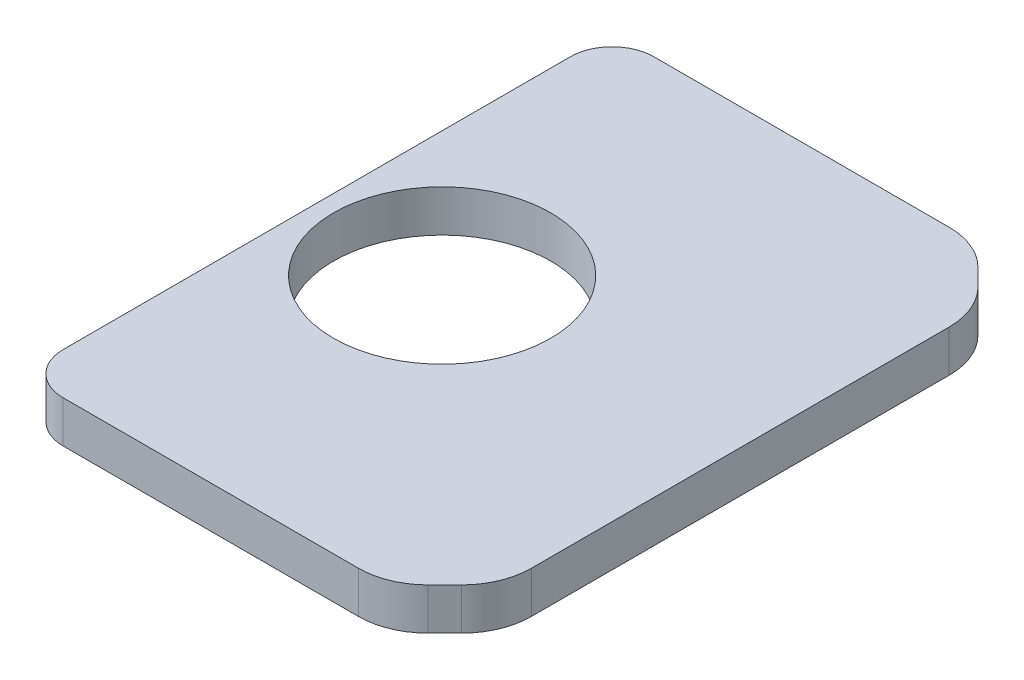
SolidWorks part; units mm, degrees
material "ABS"
ref_plane "Płaszczyzna przednia" through (0, 0, 0) normal (0, 0, 1) x (1, 0, 0)
ref_plane "Płaszczyzna górna" through (0, 0, 0) normal (0, 1, 0) x (1, 0, 0)
ref_plane "Płaszczyzna prawa" through (0, 0, 0) normal (1, 0, 0) x (0, 0, -1)
sketch "Szkic1" plane through (0, 0, 0) normal (0, 1, 0) x (1, 0, 0)
  line L0 (-23.0519, -6.1039) -> (-18.7428, -1.7948) construction
  line L1 (-23.0519, 36.8961) -> (-42.4428, 36.8961) construction
  line L2 (-23.0519, 36.8961) -> (-18.7428, 32.587) construction
  line L3 (-61.6428, 26.3906) -> (-61.6428, 4.4016)
  line L4 (-42.4428, -5.8039) -> (-57.5228, -5.8039)
  line L5 (-61.9428, 26.3906) -> (-61.9428, 4.4016) construction
  line L6 (-42.4428, -5.8039) -> (-23.1762, -5.8039)
  line L7 (-23.1762, -5.8039) -> (-19.0428, -1.6705)
  line L8 (-19.0428, -1.6705) -> (-19.0428, 32.4627)
  line L9 (-42.4428, -6.1039) -> (-23.0519, -6.1039) construction
  line L10 (-23.1762, 36.5961) -> (-19.0428, 32.4627)
  line L11 (-18.7428, -1.7948) -> (-18.7428, 32.587) construction
  line L12 (-42.4428, 36.8961) -> (-57.6495, 36.8961) construction
  line L13 (-42.4428, -6.1039) -> (-57.6495, -6.1039) construction
  line L14 (-23.1762, 36.5961) -> (-42.4428, 36.5961)
  line L15 (-42.4428, 36.5961) -> (-57.5228, 36.5961)
  circle A0 centre (-40.4428, 15.3961) radius 11.3
  circle A1 centre (-40.4428, 15.3961) radius 12.25
  circle A2 centre (-24.9428, -0.1039) radius 1.65
  circle A3 centre (-24.9428, 30.8961) radius 1.65
  circle A4 centre (-55.9428, 30.8961) radius 1.65
  circle A5 centre (-55.9428, -0.1039) radius 1.65
  arc A6 (-61.6428, 4.4016) -> (-57.5228, -5.8039) centre (-46.9428, 4.4016) ccw
  arc A7 (-57.5228, 36.5961) -> (-61.6428, 26.3906) centre (-46.9428, 26.3906) ccw
  arc A11 (-57.6495, 36.8961) -> (-61.9428, 26.3906) centre (-46.9428, 26.3906) ccw construction
  arc A12 (-61.9428, 4.4016) -> (-57.6495, -6.1039) centre (-46.9428, 4.4016) ccw construction
  circle A18 centre (-40.4428, 15.3961) radius 7.7989
  dimension "D1" = 0.3
extrude "Dodanie-wyciągnięcie1" add sketch "Szkic1" along normal blind 3 contours L5 A12 L13 L9 L0 L11 L2 L1 L12 A11 A1 A2 A3 A4 A5 | A1 A0 | A0 A18
fillet "Zaokrąglenie1" radius 5 6 edges at (-23.1762, 1.5, -36.5961) (-19.0428, 1.5, -32.4627) (-19.0428, 1.5, 1.6705) (-23.1762, 1.5, 5.8039) (-57.5228, 1.5, 5.8039) (-57.5228, 1.5, -36.5961)
sketch "Szkic2" plane through (0, 0, 0) normal (0, -1, 0) x (1, 0, 0)
  line L0 (-49.4428, -25.9584) -> (-49.4428, -38.8645) construction
  line L1 (-49.4428, 8.0723) -> (-49.4428, -4.8338) construction
  line L2 (-55.1277, -36.5961) -> (-25.2472, -36.5961) construction
  line L3 (-21.7117, -35.1317) -> (-20.5072, -33.9272) construction
  line L4 (-19.0428, -30.3917) -> (-19.0428, -0.4006) construction
  line L5 (-20.5072, 3.135) -> (-21.7117, 4.3394) construction
  line L6 (-25.2472, 5.8039) -> (-55.1277, 5.8039) construction
  line L7 (-61.6428, -4.4016) -> (-61.6428, -26.3906) construction
  line L8 (-49.4428, 8.0723) -> (-49.4428, -38.8645)
  line L9 (-49.4428, -38.8645) -> (-72.1183, -38.8645)
  line L10 (-72.1183, -38.8645) -> (-72.1183, 8.0723)
  line L11 (-72.1183, 8.0723) -> (-49.4428, 8.0723)
  arc A0 (-25.2472, -36.5961) -> (-21.7117, -35.1317) centre (-25.2472, -31.5961) ccw construction
  arc A1 (-20.5072, -33.9272) -> (-19.0428, -30.3917) centre (-24.0428, -30.3917) ccw construction
  arc A2 (-19.0428, -0.4006) -> (-20.5072, 3.135) centre (-24.0428, -0.4006) ccw construction
  arc A3 (-21.7117, 4.3394) -> (-25.2472, 5.8039) centre (-25.2472, 0.8039) ccw construction
  arc A4 (-55.1277, 5.8039) -> (-59.3467, 3.4871) centre (-55.1277, 0.8039) ccw construction
  arc A5 (-59.3467, 3.4871) -> (-61.6428, -4.4016) centre (-46.9428, -4.4016) ccw construction
  arc A6 (-61.6428, -26.3906) -> (-59.3467, -34.2794) centre (-46.9428, -26.3906) ccw construction
  arc A7 (-59.3467, -34.2794) -> (-55.1277, -36.5961) centre (-55.1277, -31.5961) ccw construction
extrude "Wytnij-wyciągnięcie1" cut sketch "Szkic2" against normal through all both and the other way through all
fillet "Zaokrąglenie5" radius 3 2 edges at (-49.4428, 1.5, -36.5961) (-49.4428, 1.5, 5.8039)
sketch "Szkic3" plane through (0, 0, 0) normal (0, -1, 0) x (1, 0, 0)
  line L0 (-49.4428, -33.5961) -> (-49.4428, 2.8039) construction
  line L6 (-25.2472, -36.5961) -> (-46.4428, -36.5961) construction
  line L7 (-20.5072, -33.9272) -> (-21.7117, -35.1317) construction
  line L8 (-19.0428, -0.4006) -> (-19.0428, -30.3917) construction
  line L9 (-21.7117, 4.3394) -> (-20.5072, 3.135) construction
  line L10 (-46.4428, 5.8039) -> (-25.2472, 5.8039) construction
  arc A8 (-46.4428, -36.5961) -> (-49.4428, -33.5961) centre (-46.4428, -33.5961) cw construction
  arc A9 (-21.7117, -35.1317) -> (-25.2472, -36.5961) centre (-25.2472, -31.5961) cw construction
  arc A10 (-19.0428, -30.3917) -> (-20.5072, -33.9272) centre (-24.0428, -30.3917) cw construction
  arc A11 (-20.5072, 3.135) -> (-19.0428, -0.4006) centre (-24.0428, -0.4006) cw construction
  arc A12 (-25.2472, 5.8039) -> (-21.7117, 4.3394) centre (-25.2472, 0.8039) cw construction
  arc A13 (-49.4428, 2.8039) -> (-46.4428, 5.8039) centre (-46.4428, 2.8039) cw construction
  circle A14 centre (-45.052, -30.8961) radius 1.65
  circle A15 centre (-45.052, 0.1039) radius 1.65
extrude "Wytnij-wyciągnięcie2" cut sketch "Szkic3" against normal through all
sketch "Szkic4" plane through (0, 3, 0) normal (0, 1, 0) x (1, 0, 0)
  circle A0 centre (-45.052, 30.8961) radius 1.65 construction
  circle A1 centre (-24.9428, 30.8961) radius 1.65 construction
  circle A2 centre (-24.9428, -0.1039) radius 1.65 construction
  circle A3 centre (-45.052, -0.1039) radius 1.65 construction
  circle A4 centre (-45.052, 30.8961) radius 1.65
  circle A5 centre (-24.9428, 30.8961) radius 1.65
  circle A6 centre (-24.9428, -0.1039) radius 1.65
  circle A7 centre (-45.052, -0.1039) radius 1.65
extrude "Dodanie-wyciągnięcie2" add sketch "Szkic4" against normal blind 0.2
